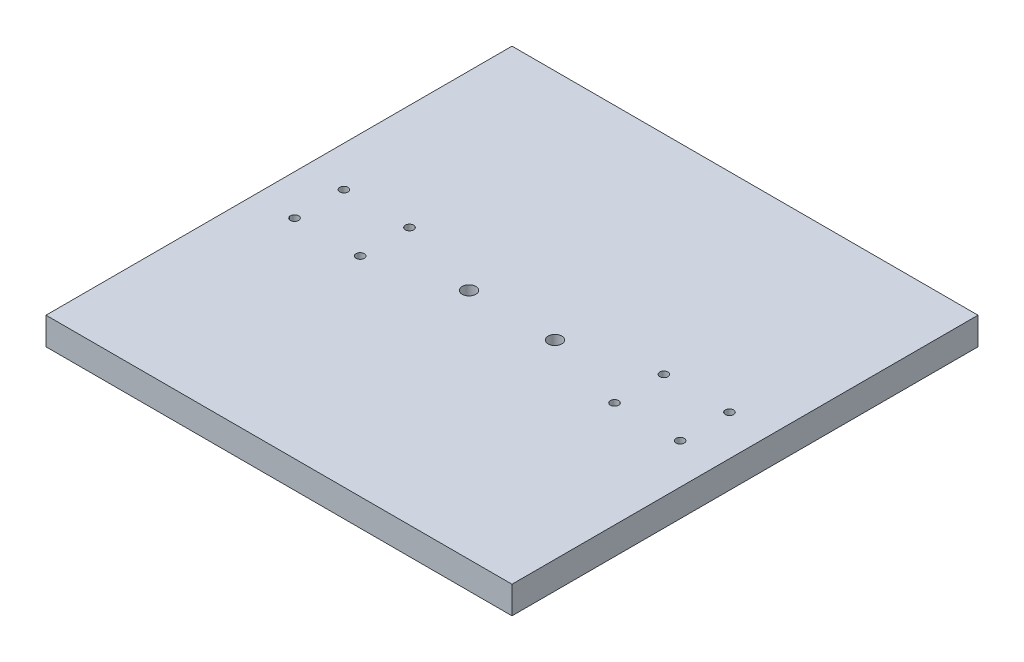
SolidWorks part; units mm, degrees
ref_plane "Front Plane" through (0, 0, 0) normal (0, 0, 1) x (1, 0, 0)
ref_plane "Top Plane" through (0, 0, 0) normal (0, 1, 0) x (1, 0, 0)
ref_plane "Right Plane" through (0, 0, 0) normal (1, 0, 0) x (0, 0, -1)
sketch "Sketch2" plane through (0, 0, 0) normal (0, 1, 0) x (1, 0, 0)
  line L1 (-85, -85) -> (85, -85)
  line L2 (-85, -85) -> (-85, 85)
  line L3 (-85, 85) -> (85, 85)
  line L4 (85, -85) -> (85, 85)
  line L5 (-85, -85) -> (85, 85) construction
  line L6 (-85, 85) -> (85, -85) construction
  point P0 (0, 0)
  dimension "D1" = 170
  dimension "D2" = 170
extrude "Boss-Extrude1" add sketch "Sketch2" along normal blind 10
sketch "Sketch4" plane through (0, 0, 0) normal (0, -1, 0) x (-1, 0, 0)
  circle A0 centre (-70.33, -9) radius 1.5
  circle A1 centre (-70.33, 9) radius 1.5
  circle A2 centre (70.33, 9) radius 1.5
  circle A3 centre (70.33, -9) radius 1.5
  circle A4 centre (46.4, 9) radius 1.5
  circle A5 centre (46.4, -9) radius 1.5
  circle A6 centre (-46.4, -9) radius 1.5
  circle A7 centre (-46.4, 9) radius 1.5
extrude "Cut-Extrude2" cut sketch "Sketch4" along normal through all and the other way through all
sketch "Sketch5" plane through (0, 0, -85) normal (0, 0, -1) x (-1, 0, 0)
  line L0 (-58, 3.5) -> (-61, 10)
  line L2 (-84, 3.5) -> (-74, 3.5)
  line L3 (-85, 10) -> (85, 10) construction
  line L4 (-81, 10) -> (-76.9988, 10)
  line L5 (-84, 3.5) -> (-81, 10)
  line L8 (-76.9988, 10) -> (-74, 3.5)
  line L11 (-58, 3.5) -> (-68, 3.5)
  line L12 (-65.0012, 10) -> (-68, 3.5)
  line L13 (-61, 10) -> (-65.0012, 10)
sketch "Sketch6" plane through (0, 0, 0) normal (0, -1, 0) x (1, 0, 0)
  line L0 (0, 0) -> (15.68, 0) construction
  line L3 (0, 0) -> (-15.68, 0) construction
  circle A0 centre (-15.68, 0) radius 2.5
  circle A1 centre (15.68, 0) radius 2.5
  dimension "D1" = 15.68
  dimension "D2" = 15.68
extrude "Cut-Extrude6" cut sketch "Sketch6" against normal blind 10
